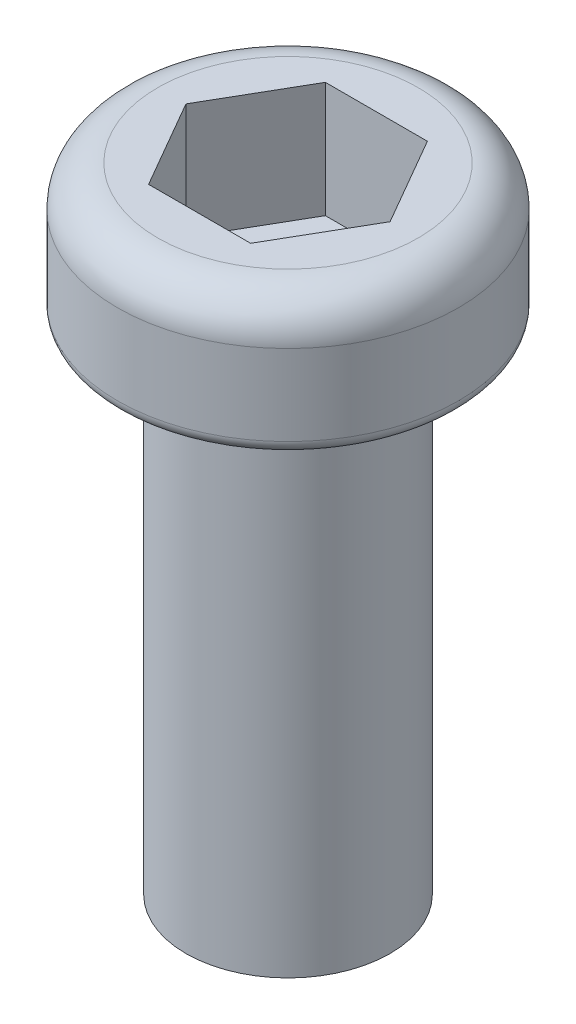
SolidWorks part; units mm, degrees
ref_plane "Front Plane" through (0, 0, 0) normal (0, 0, 1) x (1, 0, 0)
ref_plane "Top Plane" through (0, 0, 0) normal (0, 1, 0) x (1, 0, 0)
ref_plane "Right Plane" through (0, 0, 0) normal (1, 0, 0) x (0, 0, -1)
sketch "Sketch1" plane through (0, 0, 0) normal (0, 1, 0) x (1, 0, 0)
  circle A0 centre (0, 0) radius 3.175
  dimension "D1" = 6.35
extrude "Boss-Extrude3" add sketch "Sketch1" along normal blind 2.5
sketch "Sketch7" plane through (0, 2.5, 0) normal (0, 1, 0) x (1, 0, 0)
  line L1 (0.95, 1.6454) -> (-0.95, 1.6454)
  line L2 (-0.95, 1.6454) -> (-1.9, 0)
  line L3 (-1.9, 0) -> (-0.95, -1.6454)
  line L4 (-0.95, -1.6454) -> (0.95, -1.6454)
  line L5 (0.95, -1.6454) -> (1.9, 0)
  line L6 (1.9, 0) -> (0.95, 1.6454)
  circle A0 centre (0, 0) radius 1.6454 construction
  dimension "D1" = 3.8
extrude "Cut-Extrude3" cut sketch "Sketch7" against normal blind 2.15
sketch "Sketch8" plane through (0, 0, 0) normal (0, 1, 0) x (1, 0, 0)
  circle A0 centre (0, 0) radius 1.9
  dimension "D1" = 3.8
extrude "Boss-Extrude4" add sketch "Sketch8" against normal blind 9.3
fillet "Fillet2" radius 0.75 1 edges at (0, 2.5, 3.175)
fillet "Fillet3" radius 0.25 1 edges at (0, 0, 3.175)
